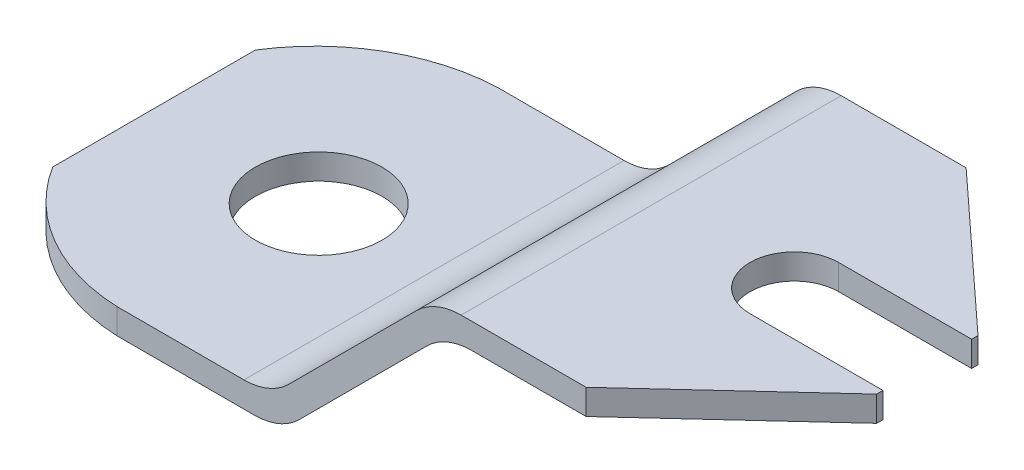
SolidWorks part; units mm, degrees
ref_plane "Alzado" through (0, 0, 0) normal (0, 0, 1) x (1, 0, 0)
ref_plane "Planta" through (0, 0, 0) normal (0, 1, 0) x (1, 0, 0)
ref_plane "Vista lateral" through (0, 0, 0) normal (1, 0, 0) x (0, 0, -1)
sketch "Croquis1" plane through (0, 0, 0) normal (0, 0, 1) x (1, 0, 0)
  line L0 (0, 0) -> (0, 53040.3568) construction
  line L1 (0, 0) -> (53040.3568, 0) construction
  line L3 (0, 0) -> (50, 0)
  line L4 (0, 0) -> (0, 4)
  line L5 (0, 4) -> (48.3431, 4)
  line L7 (50, 0) -> (76, 26)
  line L8 (48.3431, 4) -> (74.3431, 30)
  line L11 (74.3431, 30) -> (122.0865, 30)
  line L13 (76, 26) -> (122.0865, 26)
  line L14 (122.0865, 30) -> (122.0865, 26)
  point P6 (-44.973, 4.4745)
  point P13 (0, 0)
  point P15 (0, 0)
  point P16 (-147.2803, 6.8821)
  point P17 (-1.5521, 30)
  point P18 (0, 0)
  point P19 (79.7579, 26)
  point P20 (0, 0)
  dimension "D1" = 50
  dimension "D2" = 4
  dimension "D3" = 47.7434
  dimension "D4" = 30
  dimension "D5" = 4
  dimension "D6" = 26
extrude "Saliente-Extruir1" add sketch "Croquis1" along normal mid plane 60
sketch "Croquis2" plane through (0, 0, 0) normal (0, 1, 0) x (1, 0, 0)
  line L0 (0, -30) -> (0, 30) construction
  line L1 (48.3431, -30) -> (0, -30) construction
  circle A0 centre (26, 0) radius 10
  dimension "D3" = 20
  dimension "D1" = 26
  dimension "D2" = 30
extrude "Cortar-Extruir2" cut sketch "Croquis2" against normal blind 9 and the other way blind 32
sketch "Croquis3" plane through (0, 0, 0) normal (0, 1, 0) x (1, 0, 0)
  line L0 (122.0865, 0) -> (101.0865, 0) construction
  line L1 (122.0865, -30) -> (122.0865, 30) construction
  line L2 (122.0865, -7) -> (101.0865, -7)
  line L3 (122.0865, 7) -> (101.0865, 7)
  arc A0 (122.0865, -7) -> (122.0865, 7) centre (122.0865, 0) ccw
  arc A1 (101.0865, 7) -> (101.0865, -7) centre (101.0865, 0) ccw
  point P4 (111.5865, 0)
  point P9 (94.0865, 0)
  dimension "D1" = 28
  dimension "D2" = 14
extrude "Cortar-Extruir3" cut sketch "Croquis3" along normal blind 90
sketch "Croquis4" plane through (0, 0, 0) normal (0, 1, 0) x (1, 0, 0)
  line L0 (98.2148, 30) -> (122.0865, 8)
  line L5 (122.0865, 7) -> (122.0865, 30) construction
  line L6 (98.2148, 30) -> (122.0865, 30)
  line L7 (122.0865, 8) -> (122.0865, 30)
  line L8 (122.0865, -30) -> (74.3431, -30) construction
  line L9 (26, 0) -> (50026, 0) construction
  dimension "D1" = 23.8717
  dimension "D2" = 22
  dimension "D3" = 60
extrude "Cortar-Extruir4" cut sketch "Croquis4" along normal through all
mirror "Simetría1" about plane through (0, 0, 0) normal (0, 0, 1) of "Cortar-Extruir4"
sketch "Croquis5" plane through (0, 0, 0) normal (0, 1, 0) x (1, 0, 0)
  line L6 (0, 30) -> (24.1716, 30)
  line L8 (0, 30) -> (0, 16)
  line L9 (0, -30) -> (0, 30) construction
  arc A0 (24.1716, 30) -> (0, 16) centre (25.3928, 0.0249) ccw
  dimension "D3" = 30
  dimension "D1" = 14
  dimension "D2" = 24.1716
extrude "Cortar-Extruir5" cut sketch "Croquis5" along normal through all
mirror "Simetría2" about plane through (0, 0, 0) normal (0, 0, 1) of "Cortar-Extruir5"
fillet "Redondeo2" radius 10 1 edges at (48.3431, 4, 0)
fillet "Redondeo3" radius 10 1 edges at (74.3431, 30, 0)
fillet "Redondeo4" radius 10 2 edges at (76, 26, 0) (50, 0, 0)
